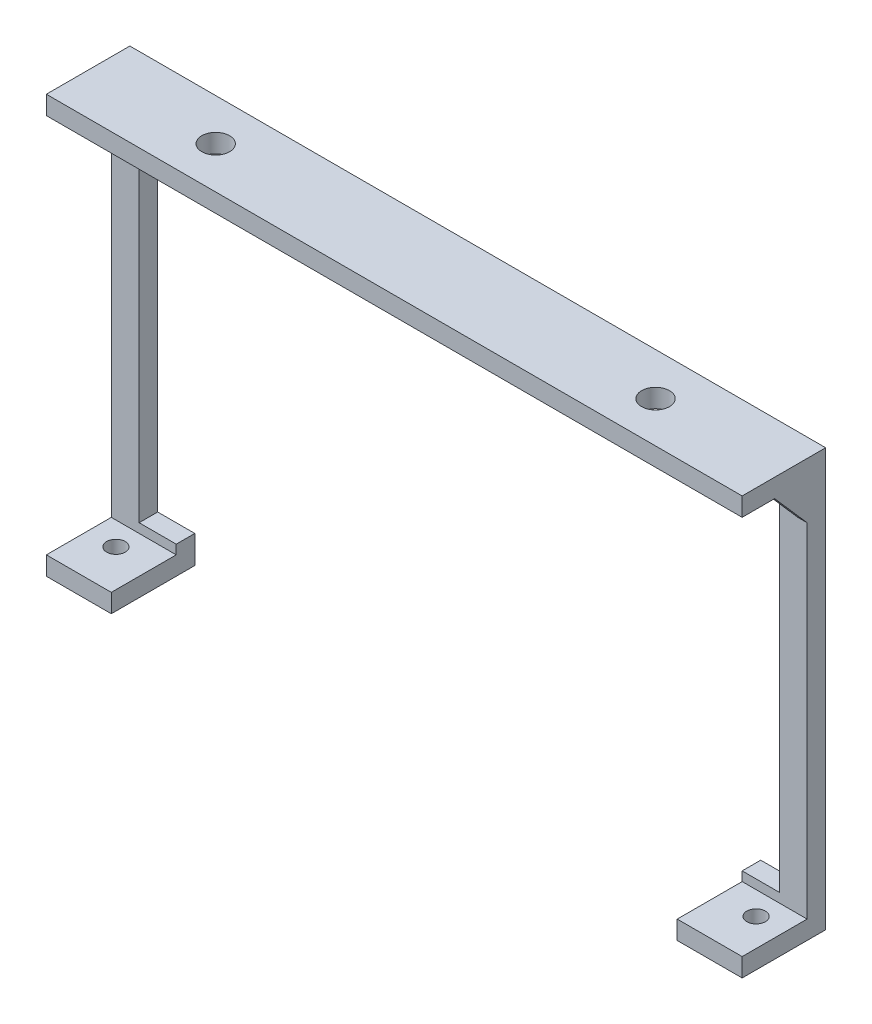
SolidWorks part; units mm, degrees
ref_plane "Front Plane" through (0, 0, 0) normal (0, 0, 1) x (1, 0, 0)
ref_plane "Top Plane" through (0, 0, 0) normal (0, 1, 0) x (1, 0, 0)
ref_plane "Right Plane" through (0, 0, 0) normal (1, 0, 0) x (0, 0, -1)
sketch "Sketch1" plane through (0, 0, 0) normal (0, 0, 1) x (1, 0, 0)
  line L0 (3, 3) -> (7, 3)
  line L1 (0, 0) -> (7, 0)
  line L2 (0, 0) -> (0, 45)
  line L3 (0, 45) -> (75, 45)
  line L4 (75, 0) -> (75, 45)
  line L5 (72, 3) -> (72, 42)
  line L6 (3, 42) -> (72, 42)
  line L7 (3, 3) -> (3, 42)
  line L8 (7, 3) -> (7, 0)
  line L9 (68, 3) -> (68, 0)
  line L10 (68, 0) -> (75, 0)
  line L11 (68, 3) -> (72, 3)
  line L12 (0, 0) -> (75, 0) construction
  line L14 (3, 3) -> (72, 3) construction
  dimension "D1" = 45
  dimension "D3" = 75
  dimension "D4" = 7
  dimension "D2" = 3
extrude "Boss-Extrude1" add sketch "Sketch1" along normal blind 2
sketch "Sketch2" plane through (0, 0, 0) normal (1, 0, 0) x (0, 0, -1)
  line L1 (-2, 45) -> (-9, 45)
  line L2 (-2, 45) -> (-2, 43)
  line L3 (-2, 43) -> (-9, 43)
  line L4 (-9, 45) -> (-9, 43)
  line L5 (-2, 0) -> (-9, 0)
  line L6 (-2, 0) -> (-2, 2)
  line L7 (-2, 2) -> (-9, 2)
  line L8 (-9, 0) -> (-9, 2)
  dimension "D1" = 2
  dimension "D2" = 7
extrude "Boss-Extrude2" add sketch "Sketch2" along normal up to surface (75 mm away) up to face at (75, 22.5, 1)
sketch "Sketch5" plane through (0, 0, 0) normal (-1, 0, 0) x (0, 0, 1)
  line L0 (5.5, 43) -> (2, 39)
  line L1 (9, 43) -> (2, 43) construction
  line L2 (2, 43) -> (2, 2) construction
  line L5 (5.5, 43) -> (2, 43)
  line L6 (2, 43) -> (2, 39)
  dimension "D2" = 4
extrude "Boss-Extrude3" add sketch "Sketch5" against normal blind 1
ref_plane "Plane1" through (37.5, 0, 0) normal (-1, 0, 0) x (0, 0, 1)
mirror "Mirror1" about plane through (37.5, 0, 0) normal (-1, 0, 0) of "Boss-Extrude3"
sketch "Sketch7" plane through (0, 45, 0) normal (0, 1, 0) x (1, 0, 0)
  line L0 (37.5, 0) -> (37.5, -9.0806) construction
  line L1 (75, 0) -> (0, 0) construction
  line L2 (37.5, 0) -> (37.5, -9.0806) construction
  line L3 (61.25, -4.586) -> (37.5, -4.5403) construction
  line L4 (37.5, -4.5403) -> (13.75, -4.4946) construction
  circle A0 centre (13.75, -4.4946) radius 1.5
  circle A1 centre (61.25, -4.586) radius 1.5
  dimension "D2" = 3
  dimension "D1" = 47.5
extrude "Cut-Extrude1" cut sketch "Sketch7" against normal up to next
sketch "Sketch8" plane through (0, 0, 0) normal (0, -1, 0) x (1, 0, 0)
  line L0 (37.5, 9) -> (37.5, 0) construction
  line L1 (75, 9) -> (0, 9) construction
  line L2 (37.5, 4.95) -> (37.5, -4.95) construction
  line L3 (3, 4.5) -> (37.5, 4.5) construction
  line L4 (37.5, 4.5) -> (72, 4.5) construction
  circle A0 centre (3, 4.5) radius 1
  circle A1 centre (72, 4.5) radius 1
  dimension "D1" = 2
  dimension "D2" = 69
extrude "Cut-Extrude2" cut sketch "Sketch8" against normal up to next
sketch "Sketch10" plane through (0, 0, 2) normal (0, 0, -1) x (-1, 0, 0)
  line L4 (-68, 0) -> (-7, 0)
  line L5 (-7, 0) -> (-7, 2)
  line L6 (-7, 2) -> (-68, 2)
  line L7 (-68, 2) -> (-68, 0)
  line L8 (-68, 0) -> (-7, 0)
  line L9 (-7, 0) -> (-7, 2)
  line L10 (-7, 2) -> (-68, 2)
  line L11 (-68, 2) -> (-68, 0)
  dimension "D1" = 0
extrude "Cut-Extrude3" cut sketch "Sketch10" against normal through all
